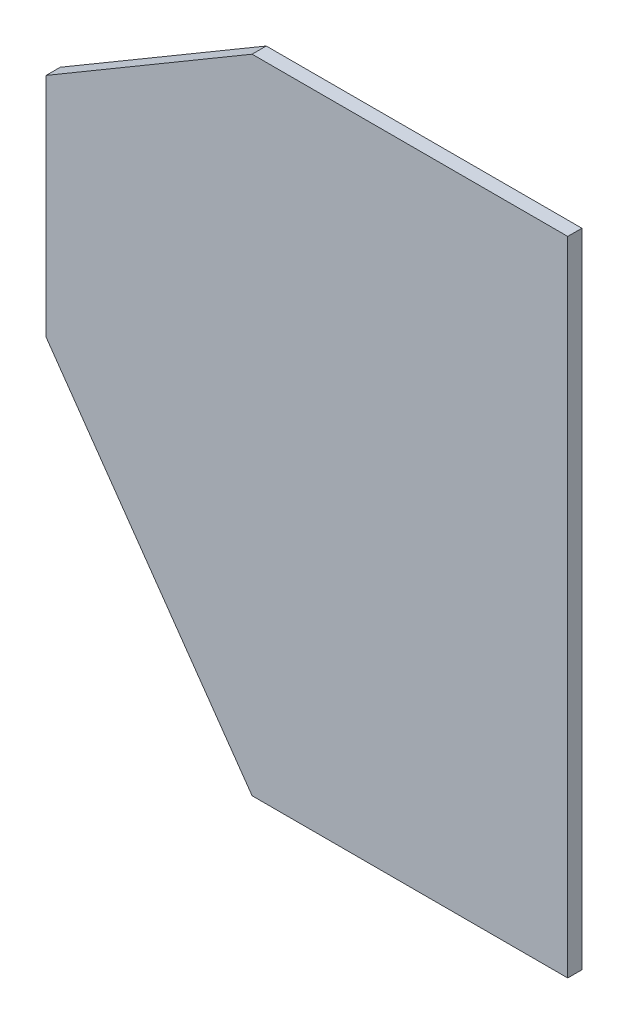
SolidWorks part; units mm, degrees
material "ASTM A500 Grade B"
ref_plane "Front Plane" through (0, 0, 0) normal (0, 0, 1) x (1, 0, 0)
ref_plane "Top Plane" through (0, 0, 0) normal (0, 1, 0) x (1, 0, 0)
ref_plane "Right Plane" through (0, 0, 0) normal (1, 0, 0) x (0, 0, -1)
sketch "Sketch1" plane through (0, 0, 0) normal (0, 0, 1) x (1, 0, 0)
  line L0 (-4.281, -202.3528) -> (-216.4881, -202.3528)
  line L1 (-4.281, -2542.8528) -> (-4.281, 2569.9472) construction
  line L2 (-216.4881, 229.4472) -> (-354.9957, 147.8379)
  line L4 (-354.9957, 147.8379) -> (-354.9957, -4.5621)
  line L6 (-354.9957, -4.5621) -> (-216.4881, -202.3528)
  line L7 (-216.4881, 229.4472) -> (-4.281, 229.4472)
  line L8 (-4.281, 229.4472) -> (-4.281, -202.3528)
  line L9 (-60.0478, 13.5472) -> (35.4026, 13.5472) construction
  line L10 (-60.0478, 73.8722) -> (-60.0478, -46.7778) construction
  dimension "D1" = 215.9
  dimension "D2" = 215.9
  dimension "D3" = 152.4
extrude "Boss-Extrude1" add sketch "Sketch1" along normal blind 9.525
